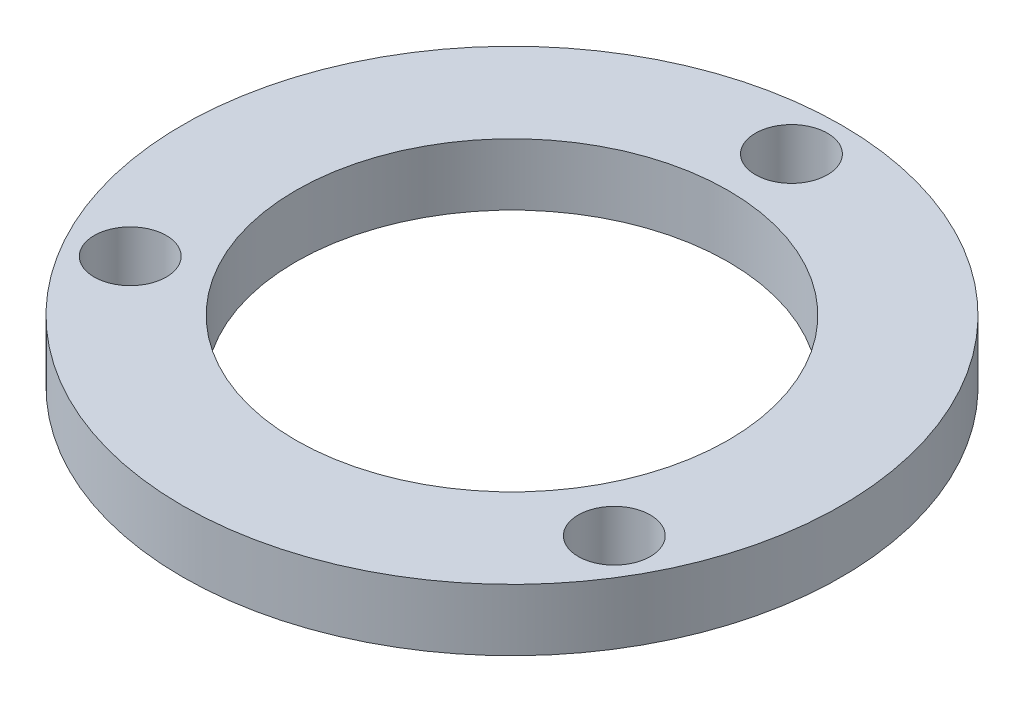
SolidWorks part; units mm, degrees
ref_plane "Front Plane" through (0, 0, 0) normal (0, 0, 1) x (1, 0, 0)
ref_plane "Top Plane" through (0, 0, 0) normal (0, 1, 0) x (1, 0, 0)
ref_plane "Right Plane" through (0, 0, 0) normal (1, 0, 0) x (0, 0, -1)
sketch "Sketch1" plane through (0, 0, 0) normal (0, 1, 0) x (1, 0, 0)
  circle A0 centre (0, 0) radius 16
  circle A1 centre (0, 0) radius 10.5
  point P5 (0, -0.2775)
  dimension "D1" = 21
  dimension "D2" = 32
extrude "Boss-Extrude1" add sketch "Sketch1" along normal blind 3
sketch "Sketch2" plane through (0, 3, 0) normal (0, 1, 0) x (1, 0, 0)
  line L0 (-11.75, -6.7839) -> (11.75, -6.7839) construction
  line L1 (11.75, -6.7839) -> (0, 13.5677) construction
  line L2 (0, 13.5677) -> (-11.75, -6.7839) construction
  circle A0 centre (0, 0) radius 13.5677 construction
  circle A1 centre (0, 13.5677) radius 1.75
  circle A2 centre (-11.75, -6.7839) radius 1.75
  circle A3 centre (11.75, -6.7839) radius 1.75
  dimension "D2" = 3.5
  dimension "D1" = 23.5
extrude "Cut-Extrude1" cut sketch "Sketch2" against normal through all
